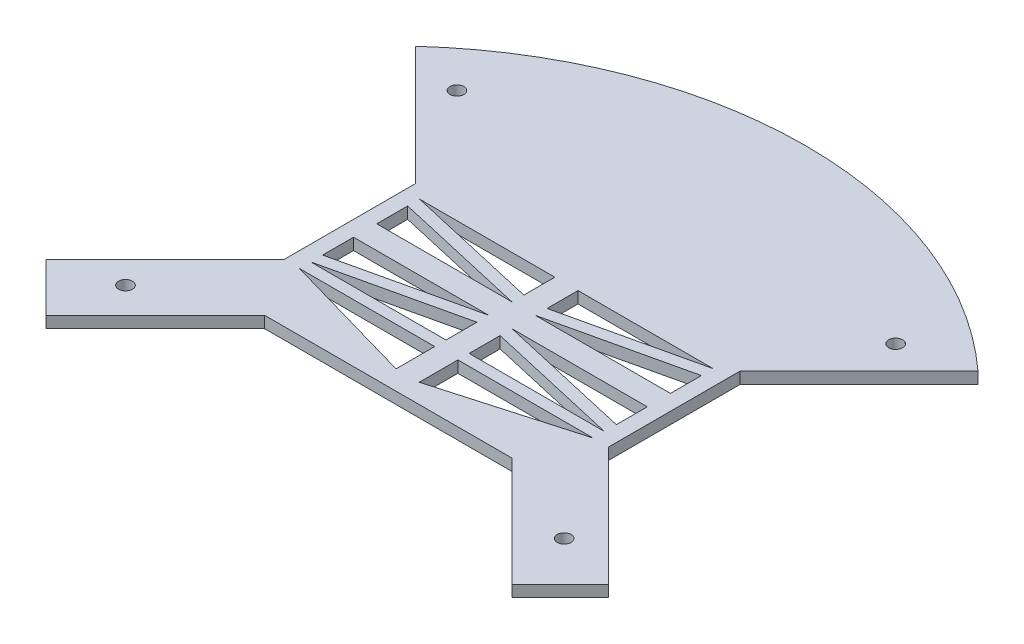
SolidWorks part; units mm, degrees
ref_plane "Front Plane" through (0, 0, 0) normal (0, 0, 1) x (1, 0, 0)
ref_plane "Top Plane" through (0, 0, 0) normal (0, 1, 0) x (1, 0, 0)
ref_plane "Right Plane" through (0, 0, 0) normal (1, 0, 0) x (0, 0, -1)
sketch "Sketch2" plane through (0, 0, 0) normal (0, 1, 0) x (1, 0, 0)
  line L16 (32, 32) -> (60.2843, 60.2843)
  line L17 (-42, 32) -> (42, 32)
  line L18 (-42, 32) -> (-42, -32)
  line L19 (-42, -32) -> (42, -32)
  line L20 (42, 32) -> (42, -32)
  line L21 (60.2843, 60.2843) -> (72.7843, 47.7843)
  line L22 (72.7843, 47.7843) -> (42, 17)
  line L23 (-86.7009, 0) -> (97.948, 0) construction
  line L24 (0, -48.5889) -> (0, 60.2843) construction
  line L25 (72.7843, -47.7843) -> (42, -17)
  line L26 (60.2843, -60.2843) -> (72.7843, -47.7843)
  line L27 (32, -32) -> (60.2843, -60.2843)
  line L28 (-60.2843, -60.2843) -> (-72.7843, -47.7843)
  line L29 (-72.7843, -47.7843) -> (-42, -17)
  line L30 (-32, -32) -> (-60.2843, -60.2843)
  line L31 (-72.7843, 47.7843) -> (-42, 17)
  line L32 (-60.2843, 60.2843) -> (-72.7843, 47.7843)
  line L33 (-32, 32) -> (-60.2843, 60.2843)
  arc A0 (72.7843, 47.7843) -> (-72.7843, 47.7843) centre (0, -32) ccw
  dimension "D1" = 84
  dimension "D2" = 64
  dimension "D3" = 42
  dimension "D4" = 32
  dimension "D5" = 10
  dimension "D6" = 15
  dimension "D7" = 40
  dimension "D8" = 45
extrude "Boss-Extrude1" add sketch "Sketch2" along normal blind 3 contours L20 L17 L18 L19 | L30 L19 L18 L29 L28 | L22 L21 L16 L17 L20 | L19 L27 L26 L25 L20 | L17 L33 L32 L31 L18 | L16 A0 L33 L17
sketch "Sketch5" plane through (0, 3, 0) normal (0, 1, 0) x (1, 0, 0)
  circle A0 centre (-57.5, 43.25) radius 1.8
  circle A1 centre (56, 43.25) radius 1.8
  circle A2 centre (56.75, -43.25) radius 1.8
  circle A3 centre (-56.75, -43.25) radius 1.8
  dimension "D1" = 3.6
  dimension "D2" = 3.6
  dimension "D3" = 3.6
  dimension "D4" = 3.6
  dimension "D5" = 113.5
  dimension "D6" = 86.5
  dimension "D7" = 57.5
  dimension "D8" = 56.75
  dimension "D9" = 43.25
  dimension "D10" = 86.5
  dimension "D11" = 43.25
  dimension "D12" = 56.75
extrude "Cut-Extrude2" cut sketch "Sketch5" against normal through all
sketch "Sketch6" plane through (0, 3, 0) normal (0, 1, 0) x (1, 0, 0)
  line L0 (-38, 14.0774) -> (-3, 14.0774)
  line L1 (-3, 14.0774) -> (-3, 6.0774)
  line L2 (-3, 6.0774) -> (-38, 14.0774)
  line L3 (-38, 11) -> (-3, 3)
  line L4 (-3, 3) -> (-38, 3)
  line L5 (-38, 3) -> (-38, 11)
  line L8 (0, -41.2379) -> (0, 55.3823) construction
  line L9 (-74.4653, 0) -> (82.0241, 0) construction
  line L10 (-3, -14.0774) -> (-3, -6.0774)
  line L11 (-38, -14.0774) -> (-3, -14.0774)
  line L12 (-3, -6.0774) -> (-38, -14.0774)
  line L13 (-3, -3) -> (-38, -3)
  line L14 (-38, -11) -> (-3, -3)
  line L15 (-38, -3) -> (-38, -11)
  line L16 (38, -14.0774) -> (3, -14.0774)
  line L17 (3, -6.0774) -> (38, -14.0774)
  line L18 (3, -14.0774) -> (3, -6.0774)
  line L19 (38, -11) -> (3, -3)
  line L20 (38, -3) -> (38, -11)
  line L21 (3, -3) -> (38, -3)
  line L22 (3, 3) -> (38, 3)
  line L23 (38, 11) -> (3, 3)
  line L24 (38, 3) -> (38, 11)
  line L25 (3, 14.0774) -> (3, 6.0774)
  line L26 (38, 14.0774) -> (3, 14.0774)
  line L27 (3, 6.0774) -> (38, 14.0774)
  line L28 (-38, -17) -> (-3, -17)
  line L29 (-3, -17) -> (-3, -27)
  line L30 (-3, -27) -> (-38, -17)
  line L31 (-42, 17) -> (-42, -17) construction
  line L32 (3, -17) -> (3, -27)
  line L33 (38, -17) -> (3, -17)
  line L34 (3, -27) -> (38, -17)
  dimension "D1" = 8
  dimension "D2" = 35
  dimension "D3" = 3
  dimension "D4" = 3
  dimension "D5" = 8
  dimension "D6" = 3
  dimension "D7" = 3
  dimension "D8" = 10
  dimension "D9" = 3
  dimension "D10" = 4
extrude "Cut-Extrude3" cut sketch "Sketch6" against normal through all
